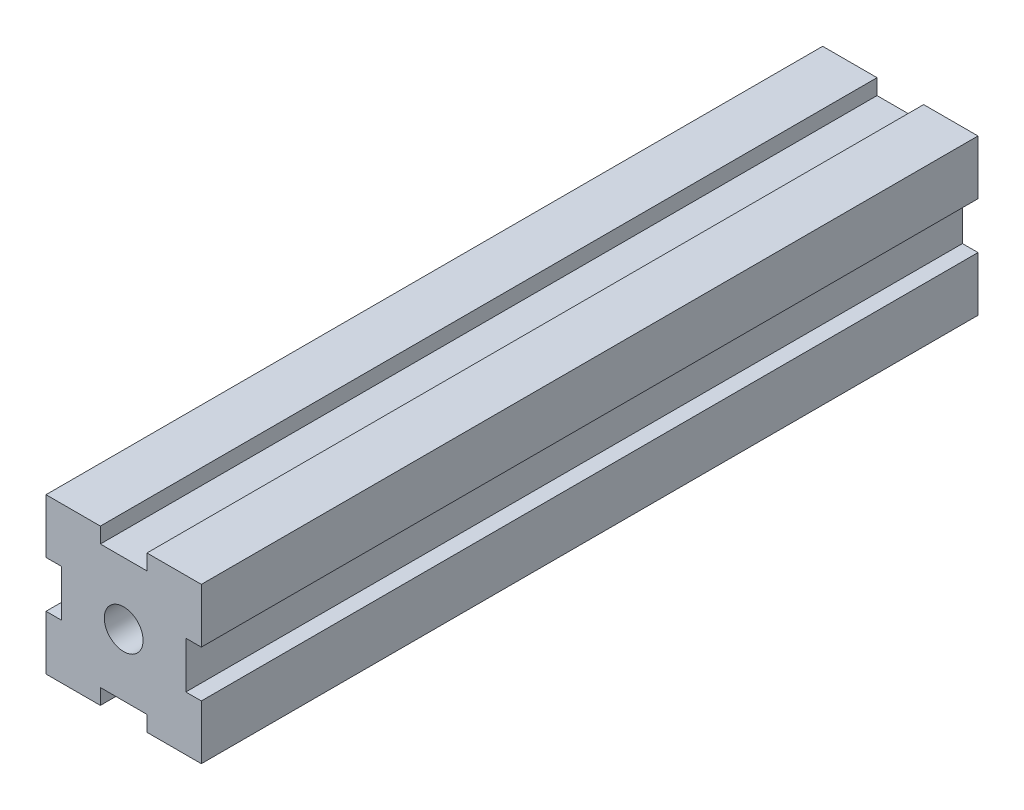
SolidWorks part; units mm, degrees
ref_plane "前视基准面" through (0, 0, 0) normal (0, 0, 1) x (1, 0, 0)
ref_plane "上视基准面" through (0, 0, 0) normal (0, 1, 0) x (1, 0, 0)
ref_plane "右视基准面" through (0, 0, 0) normal (1, 0, 0) x (0, 0, -1)
sketch "草图1" plane through (0, 0, 0) normal (0, 0, 1) x (1, 0, 0)
  line L0 (0, -13) -> (0, -20)
  line L1 (0, 0) -> (7, 0)
  line L2 (0, 0) -> (0, -7)
  line L3 (0, -20) -> (7, -20)
  line L4 (20, 0) -> (20, -7)
  line L5 (20, -7) -> (18, -7)
  line L6 (13, -20) -> (20, -20)
  line L7 (20, -13) -> (18, -13)
  line L8 (18, -7) -> (18, -13)
  line L9 (0, -7) -> (2, -7)
  line L10 (13, 0) -> (20, 0)
  line L11 (0, -13) -> (2, -13)
  line L12 (2, -7) -> (2, -13)
  line L13 (20, -13) -> (20, -20)
  line L14 (7, 0) -> (7, -2)
  line L15 (7, -2) -> (13, -2)
  line L16 (13, 0) -> (13, -2)
  line L17 (0, -7) -> (0, -13) construction
  line L18 (7, -20) -> (7, -18)
  line L19 (7, -18) -> (13, -18)
  line L20 (13, -20) -> (13, -18)
  line L21 (7, 0) -> (13, 0) construction
  line L22 (20, -7) -> (20, -13) construction
  line L23 (13, -20) -> (7, -20) construction
  line L24 (2, -10) -> (18, -10) construction
  line L25 (10, -2) -> (10, -18) construction
  circle A0 centre (10, -10) radius 2.5
  point P21 (10, 0)
  point P22 (10, -2)
  point P23 (10, -18)
  point P24 (2, -10)
  point P25 (18, -10)
  point P26 (0, -10)
  dimension "D13" = 5
  dimension "D1" = 20
  dimension "D2" = 20
  dimension "D3" = 6
  dimension "D4" = 6
  dimension "D5" = 6
  dimension "D6" = 6
  dimension "D7" = 10
  dimension "D8" = 10
  dimension "D9" = 2
  dimension "D10" = 2
  dimension "D11" = 2
  dimension "D12" = 2
extrude "凸台-拉伸1" add sketch "草图1" along normal blind 100
